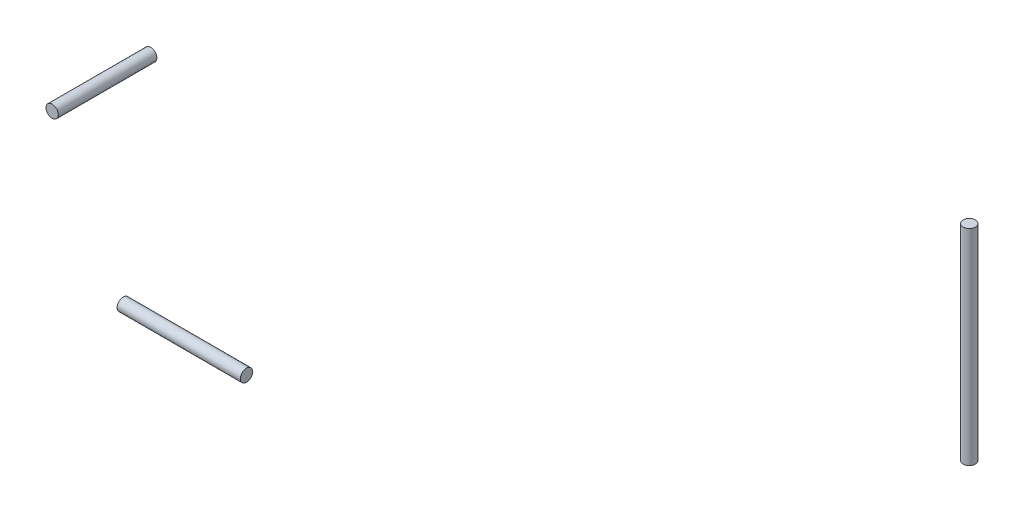
SolidWorks part; units mm, degrees
ref_plane "Front Plane" through (0, 0, 0) normal (0, 0, 1) x (1, 0, 0)
ref_plane "Top Plane" through (0, 0, 0) normal (0, 1, 0) x (1, 0, 0)
ref_plane "Right Plane" through (0, 0, 0) normal (1, 0, 0) x (0, 0, -1)
other "Configuration Table"
sketch "Sketch1" plane through (0, 0, 0) normal (0, 0, 1) x (1, 0, 0)
  circle A0 centre (66.34, 221) radius 0.75
extrude "tc1_spring" add sketch "Sketch1" along normal blind 12 from offset 38 separate body
sketch "Sketch2" plane through (0, 0, 0) normal (0, 1, 0) x (1, 0, 0)
  circle A0 centre (128, 0) radius 0.75
extrude "tc2_air" add sketch "Sketch2" along normal blind 25 from offset 190 separate body
sketch "Sketch3" plane through (0, 0, 0) normal (1, 0, 0) x (0, 0, -1)
  circle A0 centre (-64, 219) radius 0.75
extrude "tc3_reflector" add sketch "Sketch3" along normal blind 15 from offset 89 separate body
